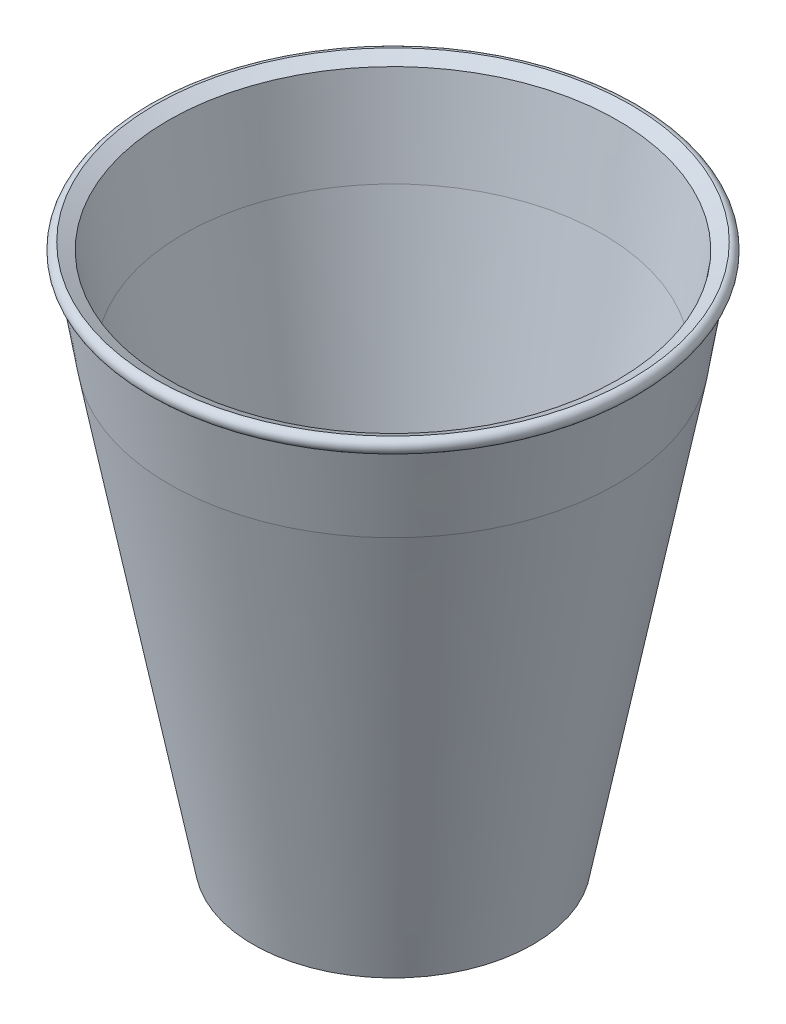
SolidWorks part; units mm, degrees
ref_plane "Front Plane" through (0, 0, 0) normal (0, 0, 1) x (1, 0, 0)
ref_plane "Top Plane" through (0, 0, 0) normal (0, 1, 0) x (1, 0, 0)
ref_plane "Right Plane" through (0, 0, 0) normal (1, 0, 0) x (0, 0, -1)
sketch "Sketch1" plane through (0, 0, 0) normal (0, 0, 1) x (1, 0, 0)
  line L0 (0, 0) -> (0, -77) construction
  line L1 (-20, -77) -> (20, -77) construction
  line L2 (-34, 0) -> (34, 0) construction
  line L3 (-32.1307, -1) -> (-34, 0)
  line L6 (21.5561, -64) -> (20, -77) construction
  line L9 (-34, -2) -> (34, -2) construction
  line L10 (-35, -1) -> (35, -1) construction
  line L11 (-32, -14) -> (32, -14) construction
  line L12 (-34, -2) -> (-32, -14)
  line L15 (34, -2) -> (32, -14) construction
  line L16 (32, -14) -> (27.5, -50.547) construction
  line L17 (27.5, -50.547) -> (23.9354, -64) construction
  line L19 (21.5561, -64) -> (23.9354, -64) construction
  line L22 (0, -74) -> (-18.5355, -74)
  line L27 (-29.964, -14) -> (-32.1307, -1)
  line L28 (-29.964, -14) -> (-18.5355, -74)
  line L29 (-20, -77) -> (-12.6, -77)
  line L30 (-12.6, -77) -> (-12.6, -75.5)
  line L31 (-12.6, -75.5) -> (0, -75.5)
  line L32 (0, -75.5) -> (0, -74)
  line L33 (-32, -14) -> (-20, -77)
  arc A0 (-34, -2) -> (-34, 0) centre (-34, -1) cw
  arc A1 (34, -2) -> (34, 0) centre (34, -1) ccw construction
  point P6 (0, -77)
  point P11 (0, 0)
  point P22 (0, -2)
  point P25 (0, -1)
  point P28 (0, -14)
  dimension "D1" = 77
  dimension "D2" = 40
  dimension "D3" = 68
  dimension "D5" = 2
  dimension "D9" = 2
  dimension "D10" = 68
  dimension "D11" = 70
  dimension "D12" = 1
  dimension "D13" = 14
  dimension "D14" = 64
  dimension "D15" = 1.5
  dimension "D20" = 12.6
  dimension "D21" = 3
revolve "Revolve1" add sketch "Sketch1" angle 360 about L0
sketch "Sketch3" plane through (0, -77, 0) normal (0, -1, 0) x (1, 0, 0)
  line L6 (-0.25, 12.5975) -> (-0.25, 11.9975)
  line L7 (-0.25, 11.9975) -> (0.25, 11.9975)
  line L8 (0.25, 12.5975) -> (0.25, 11.9975)
  circle A2 centre (0, 0) radius 12.6
  arc A3 (0.25, 12.5975) -> (-0.25, 12.5975) centre (0, 0) ccw
  point P4 (0, 12.6)
  point P7 (0, 0)
  point P8 (0, 0)
  dimension "D2" = 0.5
  dimension "D3" = 0.6
  dimension "D1" = 0
extrude "Boss-Extrude1" add sketch "Sketch3" against normal blind 0.5
sketch "Sketch8" plane through (-0.25, 0, 0) normal (-1, 0, 0) x (0, 0, 1)
  line L1 (11.9975, -76.75) -> (12.5975, -77)
  line L5 (11.9975, -77) -> (12.5975, -77)
  line L6 (12.5975, -77) -> (12.5975, -76.5)
  line L7 (12.5975, -76.5) -> (11.9975, -76.5)
  line L8 (11.9975, -76.5) -> (11.9975, -77)
  line L9 (11.9975, -77) -> (12.5975, -77)
  line L12 (11.9975, -76.75) -> (11.9975, -77)
  point P4 (11.7975, -76.5)
  dimension "D2" = 0.25
  dimension "D1" = 0
extrude "Cut-Extrude1" cut sketch "Sketch8" against normal blind 0.5
pattern_circular "CirPattern2" count 4 every 90 about axis through (0, 0, 0) along (0, 1, 0) of "Boss-Extrude1", "Cut-Extrude1"
